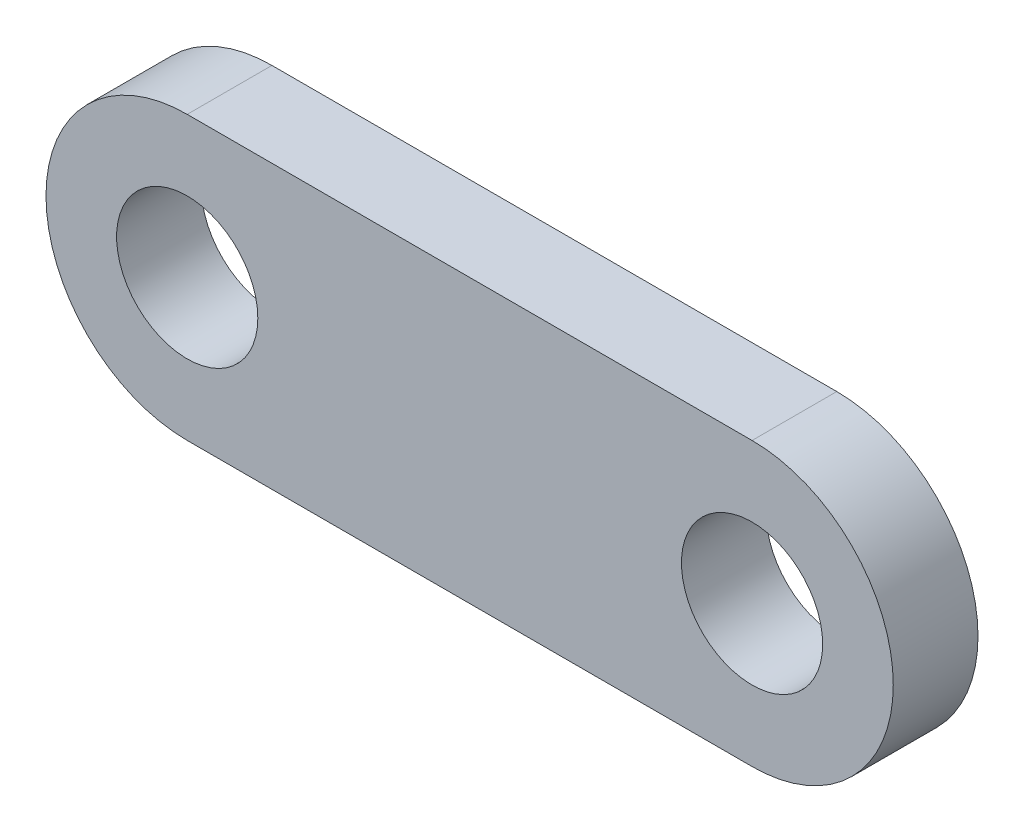
SolidWorks part; units mm, degrees
ref_plane "Front Plane" through (0, 0, 0) normal (0, 0, 1) x (1, 0, 0)
ref_plane "Top Plane" through (0, 0, 0) normal (0, 1, 0) x (1, 0, 0)
ref_plane "Right Plane" through (0, 0, 0) normal (1, 0, 0) x (0, 0, -1)
sketch "Sketch1" plane through (0, 0, 0) normal (0, 0, 1) x (1, 0, 0)
  line L0 (-10, 0) -> (10, 0) construction
  line L1 (-10, 5) -> (10, 5)
  line L2 (-10, -5) -> (10, -5)
  arc A0 (-10, 5) -> (-10, -5) centre (-10, 0) ccw
  arc A1 (10, -5) -> (10, 5) centre (10, 0) ccw
  circle A2 centre (-10, 0) radius 2.5
  circle A3 centre (10, 0) radius 2.5
  point P2 (0, 0)
  dimension "D2" = 5
  dimension "D3" = 5
  dimension "D4" = 5
  dimension "D1" = 20
extrude "Boss-Extrude1" add sketch "Sketch1" along normal blind 3
